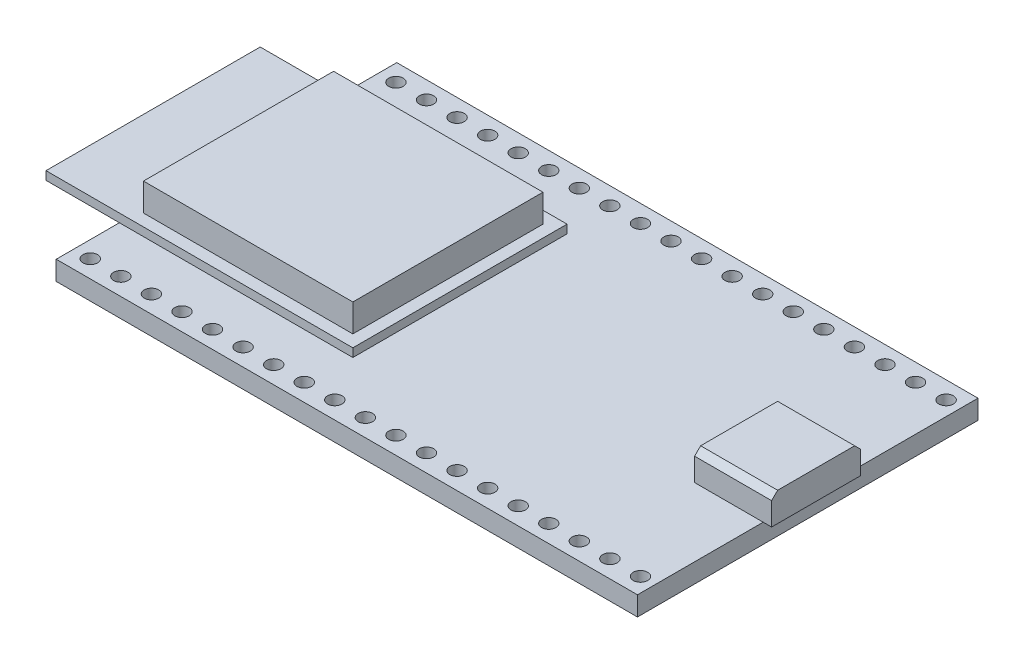
SolidWorks part; units mm, degrees
ref_plane "前视基准面" through (0, 0, 0) normal (0, 0, 1) x (1, 0, 0)
ref_plane "上视基准面" through (0, 0, 0) normal (0, 1, 0) x (1, 0, 0)
ref_plane "右视基准面" through (0, 0, 0) normal (1, 0, 0) x (0, 0, -1)
other "Configuration Table"
sketch "草图1" plane through (0, 0, 0) normal (0, 1, 0) x (1, 0, 0)
  line L1 (-24.15, 14.15) -> (24.15, 14.15)
  line L2 (-24.15, 14.15) -> (-24.15, -14.15)
  line L3 (-24.15, -14.15) -> (24.15, -14.15)
  line L4 (24.15, 14.15) -> (24.15, -14.15)
  line L5 (-24.15, 14.15) -> (24.15, -14.15) construction
  line L6 (-24.15, -14.15) -> (24.15, 14.15) construction
  point P0 (0, 0)
  dimension "D1" = 48.3
  dimension "D2" = 28.3
extrude "凸台-拉伸1" add sketch "草图1" along normal blind 1.6
sketch "草图3" plane through (0, 1.6, 0) normal (0, 1, 0) x (1, 0, 0)
  line L0 (-24.15, 0) -> (24.15, 0) construction
  line L1 (-24.15, 14.15) -> (-24.15, -14.15) construction
  line L2 (24.15, -14.15) -> (24.15, 14.15) construction
  line L4 (-30.25, 8.9) -> (-4.75, 8.9)
  line L5 (-30.25, 8.9) -> (-30.25, -8.9)
  line L6 (-30.25, -8.9) -> (-4.75, -8.9)
  line L7 (-4.75, 8.9) -> (-4.75, -8.9)
  line L8 (-30.25, 8.9) -> (-4.75, -8.9) construction
  line L9 (-30.25, -8.9) -> (-4.75, 8.9) construction
  point P6 (-17.5, 0)
  dimension "D1" = 25.5
  dimension "D2" = 17.8
  dimension "D3" = 6.1
extrude "凸台-拉伸2" add sketch "草图3" along normal blind 0.7
sketch "草图4" plane through (0, 2.3, 0) normal (0, 1, 0) x (1, 0, 0)
  line L0 (-24.15, 0) -> (-4.75, 0) construction
  line L1 (-4.75, 8.9) -> (-24.15, 8.9)
  line L2 (-4.75, 8.9) -> (-4.75, -8.9)
  line L3 (-4.75, -8.9) -> (-24.15, -8.9)
  line L4 (-24.15, 8.9) -> (-24.15, -8.9)
  line L5 (-4.75, 0) -> (-14.45, 8.9) construction
  line L6 (-14.45, 8.9) -> (-14.45, -8.9) construction
  line L8 (-23.15, 7.9) -> (-5.75, 7.9)
  line L9 (-23.15, 7.9) -> (-23.15, -7.9)
  line L10 (-23.15, -7.9) -> (-5.75, -7.9)
  line L11 (-5.75, 7.9) -> (-5.75, -7.9)
  line L12 (-23.15, 7.9) -> (-5.75, -7.9) construction
  line L13 (-23.15, -7.9) -> (-5.75, 7.9) construction
  point P10 (-14.45, 0)
  dimension "D1" = 1
  dimension "D2" = 1
extrude "凸台-拉伸3" add sketch "草图4" along normal blind 2.3 contours L11 L8 L9 L10
sketch "草图5" plane through (0, 1.6, 0) normal (0, 1, 0) x (1, 0, 0)
  line L0 (0, 0) -> (24.15, 0) construction
  line L1 (24.15, -14.15) -> (24.15, 14.15) construction
  line L3 (18.45, 3.7) -> (24.85, 3.7)
  line L4 (18.45, 3.7) -> (18.45, -3.7)
  line L5 (18.45, -3.7) -> (24.85, -3.7)
  line L6 (24.85, 3.7) -> (24.85, -3.7)
  line L7 (18.45, 3.7) -> (24.85, -3.7) construction
  line L8 (18.45, -3.7) -> (24.85, 3.7) construction
  point P5 (21.65, 0)
  dimension "D1" = 7.4
  dimension "D2" = 6.4
  dimension "D3" = 0.7
extrude "凸台-拉伸4" add sketch "草图5" along normal blind 2.4
chamfer "倒角1" distance 0.5 angle 45 2 edges at (21.65, 4, -3.7) (21.65, 4, 3.7)
sketch "草图6" plane through (0, 1.6, 0) normal (0, 1, 0) x (1, 0, 0)
  line L0 (0, 0) -> (24.85, 0) construction
  line L1 (24.85, -3.2) -> (24.85, 3.2) construction
  line L2 (12.425, 0) -> (12.425, 12.7) construction
  line L3 (12.425, 12.7) -> (22.95, 12.7) construction
  line L4 (24.15, 3.7) -> (24.15, 14.15) construction
  circle A0 centre (22.95, 12.7) radius 0.6
  circle A1 centre (20.41, 12.7) radius 0.6
  circle A2 centre (17.87, 12.7) radius 0.6
  circle A3 centre (15.33, 12.7) radius 0.6
  circle A4 centre (12.79, 12.7) radius 0.6
  circle A5 centre (10.25, 12.7) radius 0.6
  circle A6 centre (7.71, 12.7) radius 0.6
  circle A7 centre (5.17, 12.7) radius 0.6
  circle A8 centre (2.63, 12.7) radius 0.6
  circle A9 centre (0.09, 12.7) radius 0.6
  circle A10 centre (-2.45, 12.7) radius 0.6
  circle A11 centre (-4.99, 12.7) radius 0.6
  circle A12 centre (-7.53, 12.7) radius 0.6
  circle A13 centre (-10.07, 12.7) radius 0.6
  circle A14 centre (-12.61, 12.7) radius 0.6
  circle A15 centre (-15.15, 12.7) radius 0.6
  circle A16 centre (-17.69, 12.7) radius 0.6
  circle A17 centre (-20.23, 12.7) radius 0.6
  circle A18 centre (-22.77, 12.7) radius 0.6
  circle A19 centre (20.41, -12.7) radius 0.6
  circle A20 centre (17.87, -12.7) radius 0.6
  circle A21 centre (15.33, -12.7) radius 0.6
  circle A22 centre (12.79, -12.7) radius 0.6
  circle A23 centre (10.25, -12.7) radius 0.6
  circle A24 centre (7.71, -12.7) radius 0.6
  circle A25 centre (5.17, -12.7) radius 0.6
  circle A26 centre (2.63, -12.7) radius 0.6
  circle A27 centre (0.09, -12.7) radius 0.6
  circle A28 centre (-2.45, -12.7) radius 0.6
  circle A29 centre (-4.99, -12.7) radius 0.6
  circle A30 centre (-7.53, -12.7) radius 0.6
  circle A31 centre (-10.07, -12.7) radius 0.6
  circle A32 centre (-12.61, -12.7) radius 0.6
  circle A33 centre (-15.15, -12.7) radius 0.6
  circle A34 centre (-17.69, -12.7) radius 0.6
  circle A35 centre (-20.23, -12.7) radius 0.6
  circle A36 centre (-22.77, -12.7) radius 0.6
  circle A37 centre (22.95, -12.7) radius 0.6
  dimension "D3" = 1.2
  dimension "D1" = 12.7
  dimension "D2" = 1.2
  dimension "D4" = 19
  dimension "D5" = 2
extrude "切除-拉伸1" cut sketch "草图6" against normal through all
